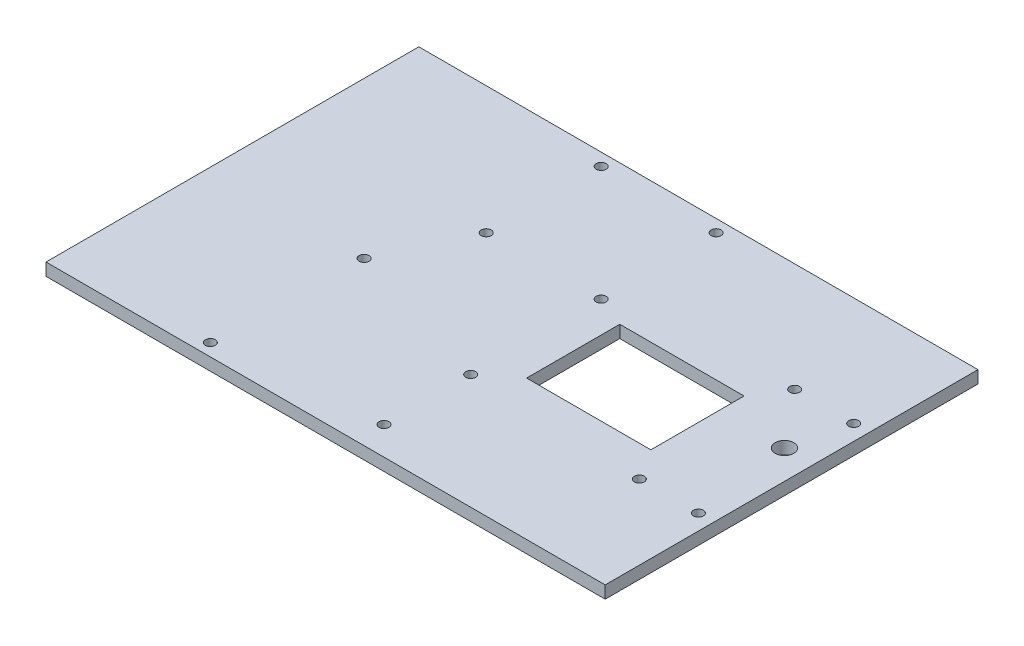
SolidWorks part; units mm, degrees
ref_plane "前视基准面" through (0, 0, 0) normal (0, 0, 1) x (1, 0, 0)
ref_plane "上视基准面" through (0, 0, 0) normal (0, 1, 0) x (1, 0, 0)
ref_plane "右视基准面" through (0, 0, 0) normal (1, 0, 0) x (0, 0, -1)
other "Configuration Table"
sketch "草图1" plane through (0, 0, 0) normal (0, 1, 0) x (1, 0, 0)
  line L1 (-90, -60) -> (90, -60)
  line L2 (-90, -60) -> (-90, 60)
  line L3 (-90, 60) -> (90, 60)
  line L4 (90, -60) -> (90, 60)
  line L5 (-90, -60) -> (90, 60) construction
  line L6 (-90, 60) -> (90, -60) construction
  point P0 (0, 0)
  dimension "D1" = 120
  dimension "D2" = 180
extrude "凸台-拉伸1" add sketch "草图1" along normal blind 4
sketch "草图2" plane through (0, 4, 0) normal (0, 1, 0) x (1, 0, 0)
  line L0 (90, -60) -> (90, 60) construction
  line L1 (66, -25) -> (85, -25) construction
  line L2 (66, -25) -> (66, 25) construction
  line L3 (66, 25) -> (85, 25) construction
  line L4 (85, -25) -> (85, 25) construction
  line L5 (66, -25) -> (85, 25) construction
  line L6 (66, 25) -> (85, -25) construction
  circle A0 centre (66, 25) radius 1.6
  circle A1 centre (66, -25) radius 1.6
  circle A2 centre (85, -25) radius 1.6
  circle A3 centre (85, 25) radius 1.6
  circle A7 centre (80.7, 7) radius 3
  point P0 (75.5, 0)
  dimension "D4" = 3.2
  dimension "D5" = 4.3
  dimension "D7" = 6
  dimension "D1" = 19
  dimension "D2" = 50
  dimension "D3" = 5
  dimension "D6" = 18
extrude "切除-拉伸1" cut sketch "草图2" against normal blind 4
sketch "草图3" plane through (0, 4, 0) normal (0, 1, 0) x (1, 0, 0)
  line L0 (90, -60) -> (90, 60) construction
  line L1 (19.7, -15) -> (59.7, -15)
  line L2 (19.7, -15) -> (19.7, 15)
  line L3 (19.7, 15) -> (59.7, 15)
  line L4 (59.7, -15) -> (59.7, 15)
  line L5 (19.7, -15) -> (59.7, 15) construction
  line L6 (19.7, 15) -> (59.7, -15) construction
  point P0 (39.7, 0)
  point P5 (0, 0)
  point P7 (-5.5563, 0)
  dimension "D1" = 40
  dimension "D2" = 30
  dimension "D3" = 50.3
extrude "切除-拉伸2" cut sketch "草图3" against normal blind 4
sketch "草图4" plane through (0, 4, 0) normal (0, 1, 0) x (1, 0, 0)
  line L0 (90, 60) -> (-90, 60) construction
  line L1 (-27.3, 56) -> (9.7, 56) construction
  line L2 (-27.3, 56) -> (-27.3, 19) construction
  line L3 (-27.3, 19) -> (9.7, 19) construction
  line L4 (9.7, 56) -> (9.7, 19) construction
  line L6 (19.7, 15) -> (19.7, -15) construction
  circle A0 centre (-27.3, 56) radius 1.6
  circle A1 centre (9.7, 56) radius 1.6
  circle A2 centre (9.7, 19) radius 1.6
  circle A3 centre (-27.3, 19) radius 1.6
  dimension "D4" = 3.2
  dimension "D1" = 37
  dimension "D2" = 4
  dimension "D3" = 10
extrude "切除-拉伸3" cut sketch "草图4" against normal blind 4
sketch "草图5" plane through (0, 4, 0) normal (0, 1, 0) x (1, 0, 0)
  line L0 (-90, -60) -> (90, -60) construction
  line L1 (-41.1, -56) -> (9.7, -56) construction
  line L2 (-41.1, -56) -> (-41.1, -7.8) construction
  line L3 (-41.1, -7.8) -> (9.7, -7.8) construction
  line L4 (9.7, -56) -> (9.7, -7.8) construction
  line L8 (19.7, 15) -> (19.7, -15) construction
  circle A0 centre (-39.8, -7.8) radius 1.6
  circle A1 centre (9.7, -23) radius 1.6
  circle A2 centre (9.7, -50.9) radius 1.6
  circle A3 centre (-41.1, -56) radius 1.6
  dimension "D8" = 3.2
  dimension "D1" = 48.2
  dimension "D2" = 50.8
  dimension "D3" = 4
  dimension "D4" = 10
  dimension "D5" = 1.3
  dimension "D6" = 15.2
  dimension "D7" = 27.9
extrude "切除-拉伸4" cut sketch "草图5" against normal blind 4
